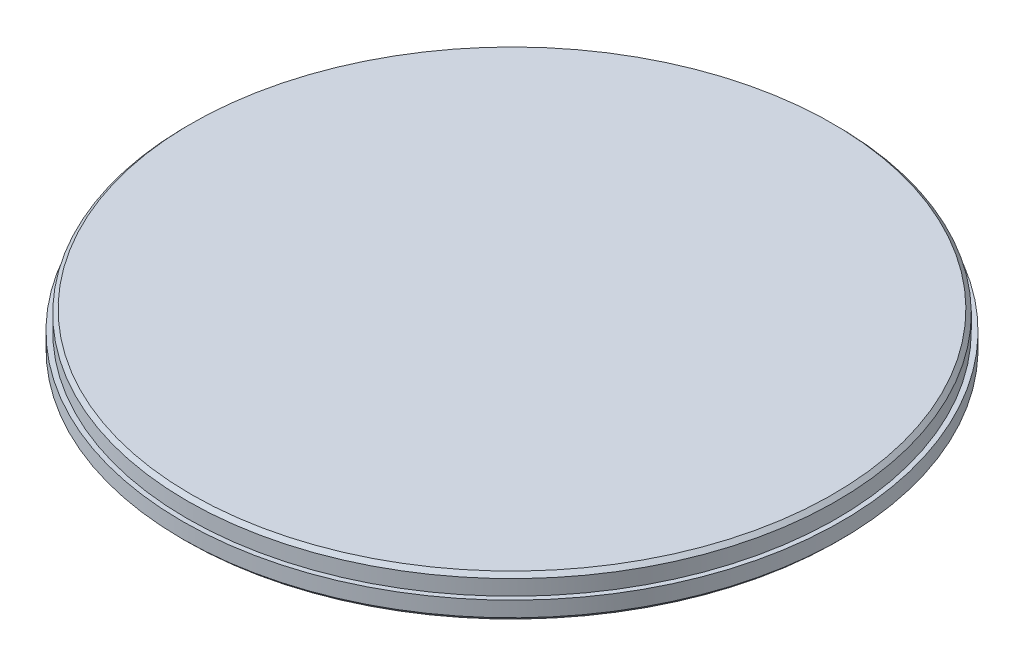
SolidWorks part; units mm, degrees
ref_plane "Front Plane" through (0, 0, 0) normal (0, 0, 1) x (1, 0, 0)
ref_plane "Top Plane" through (0, 0, 0) normal (0, 1, 0) x (1, 0, 0)
ref_plane "Right Plane" through (0, 0, 0) normal (1, 0, 0) x (0, 0, -1)
sketch "Sketch1" plane through (0, 0, 0) normal (0, 1, 0) x (1, 0, 0)
  circle A0 centre (0, 0) radius 17.25
  dimension "D1" = 34.5
extrude "Boss-Extrude1" add sketch "Sketch1" along normal blind 2
sketch "Sketch2" plane through (0, 2, 0) normal (0, 1, 0) x (1, 0, 0)
  circle A0 centre (0, 0) radius 17
  dimension "D1" = 34
extrude "Cut-Extrude1" cut sketch "Sketch2" against normal blind 1 flip side to cut
chamfer "Chamfer1" distance 0.2 angle 45 2 edges at (0, 0, 17.25) (0, 2, 17)
